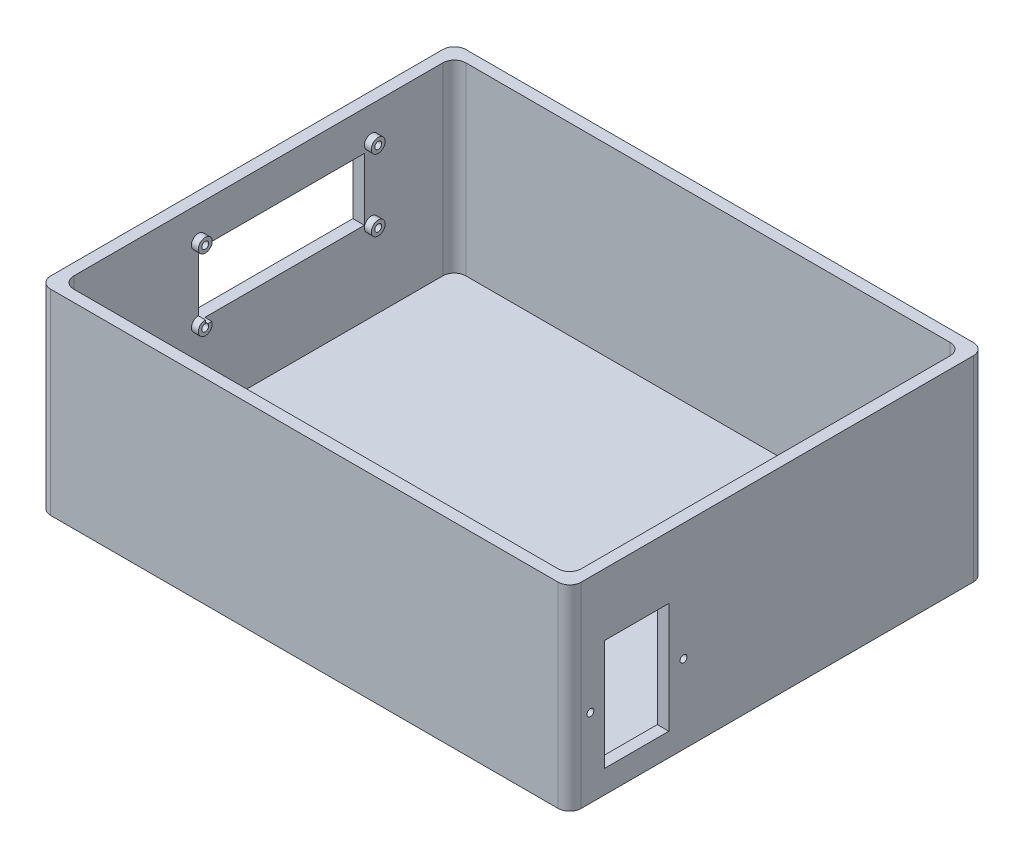
SolidWorks part; units mm, degrees
ref_plane "Front Plane" through (0, 0, 0) normal (0, 0, 1) x (1, 0, 0)
ref_plane "Top Plane" through (0, 0, 0) normal (0, 1, 0) x (1, 0, 0)
ref_plane "Right Plane" through (0, 0, 0) normal (1, 0, 0) x (0, 0, -1)
sketch "Sketch1" plane through (0, 0, 0) normal (0, 1, 0) x (1, 0, 0)
  line L1 (0, 0) -> (230, 0)
  line L2 (0, 0) -> (0, 180)
  line L3 (0, 180) -> (230, 180)
  line L4 (230, 0) -> (230, 180)
  dimension "D1" = 230
  dimension "D2" = 180
extrude "Boss-Extrude1" add sketch "Sketch1" along normal blind 5
sketch "Sketch2" plane through (0, 5, 0) normal (0, 1, 0) x (1, 0, 0)
  line L0 (5, 5) -> (5, 175)
  line L1 (0, 0) -> (230, 0)
  line L2 (0, 0) -> (0, 180)
  line L3 (0, 180) -> (230, 180)
  line L4 (230, 0) -> (230, 180)
  line L5 (5, 175) -> (225, 175)
  line L6 (225, 5) -> (225, 175)
  line L7 (5, 5) -> (225, 5)
  dimension "D1" = 5
extrude "Boss-Extrude2" add sketch "Sketch2" along normal blind 80
fillet "Fillet1" radius 5 8 edges at (5, 45, -175) (5, 45, -5) (0, 42.5, 0) (225, 45, -5) (0, 42.5, -180) (225, 45, -175) (230, 42.5, 0) (230, 42.5, -180)
sketch "Sketch3" plane through (230, 0, 0) normal (1, 0, 0) x (0, 0, -1)
  line L1 (15, 58) -> (43, 58)
  line L2 (15, 58) -> (15, 10)
  line L3 (15, 10) -> (43, 10)
  line L4 (43, 58) -> (43, 10)
  dimension "D1" = 48
  dimension "D2" = 28
  dimension "D3" = 10
  dimension "D4" = 15
extrude "Cut-Extrude1" cut sketch "Sketch3" against normal blind 5
sketch "Sketch4" plane through (230, 0, 0) normal (1, 0, 0) x (0, 0, -1)
  circle A0 centre (9, 34) radius 1.5
  circle A1 centre (49.4, 34) radius 1.5
  dimension "D1" = 3
  dimension "D2" = 3
  dimension "D3" = 40.4
  dimension "D4" = 34
  dimension "D5" = 9
extrude "Cut-Extrude2" cut sketch "Sketch4" against normal blind 5
sketch "Sketch7" plane through (5, 0, 0) normal (1, 0, 0) x (0, 0, -1)
  circle A0 centre (139, 40) radius 3
  circle A1 centre (139, 71) radius 3
  circle A2 centre (64, 71) radius 3
  circle A3 centre (64, 40) radius 3
  dimension "D7" = 6
  dimension "D8" = 6
  dimension "D9" = 6
  dimension "D10" = 6
  dimension "D1" = 40
  dimension "D2" = 64
  dimension "D3" = 31
  dimension "D4" = 75
  dimension "D5" = 75
  dimension "D6" = 64
  dimension "D11" = 40
  dimension "D12" = 31
extrude "Boss-Extrude3" add sketch "Sketch7" along normal blind 3
sketch "Sketch5" plane through (0, 0, 0) normal (-1, 0, 0) x (0, 0, 1)
  line L1 (-136, 68) -> (-64, 68)
  line L2 (-136, 68) -> (-136, 41)
  line L3 (-136, 41) -> (-64, 41)
  line L4 (-64, 68) -> (-64, 41)
  point P12 (0, 0)
  dimension "D9" = 27
  dimension "D10" = 41
  dimension "D11" = 64
  dimension "D12" = 72
extrude "Cut-Extrude3" cut sketch "Sketch5" against normal blind 10
sketch "Sketch8" plane through (8, 0, 0) normal (1, 0, 0) x (0, 0, -1)
  circle A0 centre (64, 40) radius 1.5
  circle A1 centre (139, 40) radius 1.5
  circle A2 centre (139, 71) radius 1.5
  circle A3 centre (64, 71) radius 1.5
  point P9 (0, 0)
  dimension "D5" = 3
  dimension "D6" = 3
  dimension "D7" = 3
  dimension "D8" = 3
  dimension "D1" = 31
  dimension "D2" = 75
  dimension "D3" = 75
  dimension "D4" = 31
  dimension "D9" = 64
  dimension "D10" = 40
extrude "Cut-Extrude4" cut sketch "Sketch8" against normal blind 5
